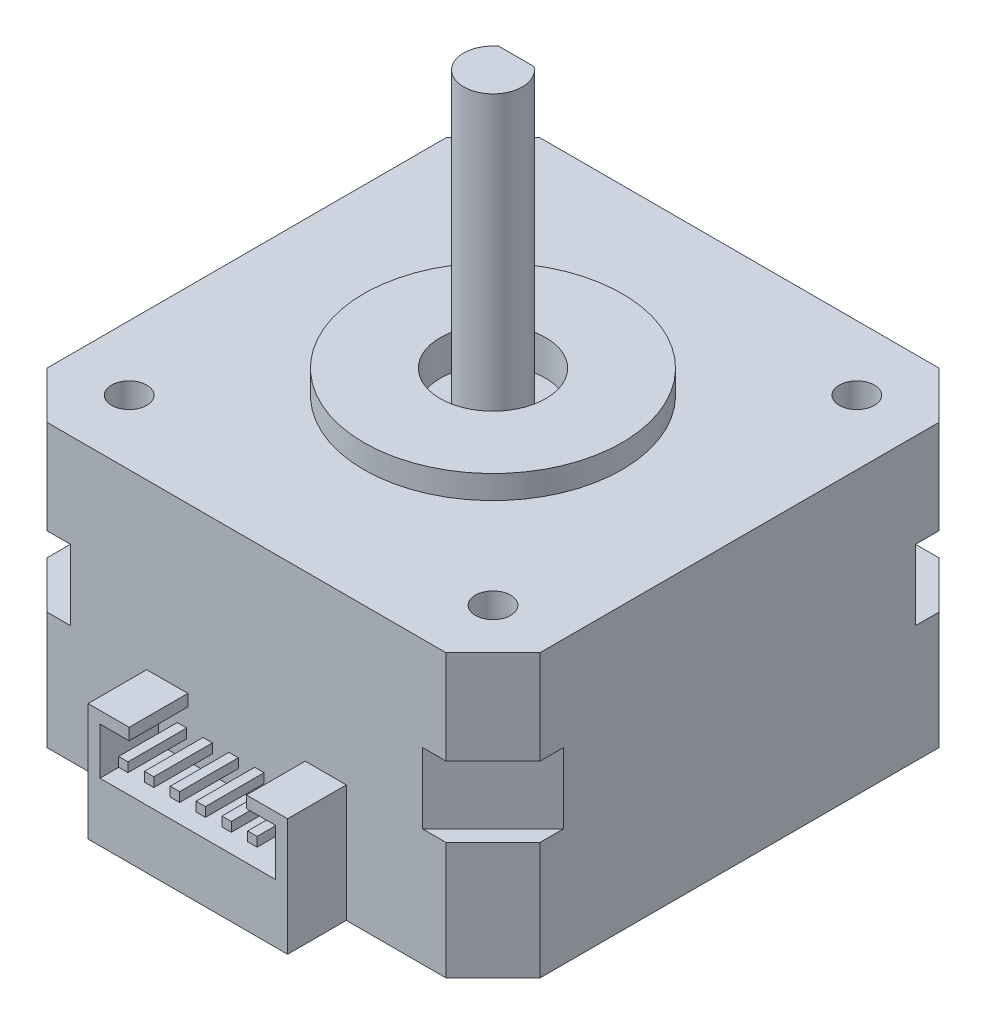
SolidWorks part; units mm, degrees
ref_plane "前视基准面" through (0, 0, 0) normal (0, 0, 1) x (1, 0, 0)
ref_plane "上视基准面" through (0, 0, 0) normal (0, 1, 0) x (1, 0, 0)
ref_plane "右视基准面" through (0, 0, 0) normal (1, 0, 0) x (0, 0, -1)
sketch "草图1" plane through (0, 0, 0) normal (0, 1, 0) x (1, 0, 0)
  line L0 (17, 21) -> (21, 17)
  line L1 (-17, -21) -> (17, -21)
  line L2 (-21, -17) -> (-21, 17)
  line L3 (-17, 21) -> (17, 21)
  line L4 (21, -17) -> (21, 17)
  line L5 (-19, -19) -> (19, 19) construction
  line L6 (-19, 19) -> (19, -19) construction
  line L7 (-21, 17) -> (-17, 21)
  line L8 (-21, -17) -> (-17, -21)
  line L9 (-17, -21) -> (17, -21)
  line L10 (17, -21) -> (21, -17)
  point P0 (0, 0)
extrude "凸台-拉伸1" add sketch "草图1" along normal blind 10 contours L1 L10 L4 L0 L3 L7 L2 L8
sketch "草图3" plane through (0, 10, 0) normal (0, 1, 0) x (1, 0, 0)
  line L0 (15, 21) -> (21, 15)
  line L1 (21, -15) -> (15, -21)
  line L2 (-15, -21) -> (-21, -15)
  line L3 (-21, 15) -> (-15, 21)
  line L8 (-17, -21) -> (17, -21)
  line L9 (17, -21) -> (21, -17)
  line L10 (21, -17) -> (21, 17)
  line L11 (21, 17) -> (17, 21)
  line L12 (17, 21) -> (-17, 21)
  line L13 (-17, 21) -> (-21, 17)
  line L14 (-21, 17) -> (-21, -17)
  line L15 (-21, -17) -> (-17, -21)
  line L16 (-15, -21) -> (15, -21)
  line L18 (21, -15) -> (21, 15)
  line L20 (15, 21) -> (-15, 21)
  line L22 (-21, 15) -> (-21, -15)
  dimension "D2" = 2
  dimension "D3" = 2
  dimension "D1" = 0
  dimension "D4" = 4
extrude "凸台-拉伸2" add sketch "草图3" along normal blind 6
sketch "草图4" plane through (0, 16, 0) normal (0, 1, 0) x (1, 0, 0)
  line L0 (15, 21) -> (17, 21) construction
  line L1 (17, 21) -> (21, 17) construction
  line L2 (21, 15) -> (21, 17) construction
  line L3 (21, -17) -> (21, -15) construction
  line L4 (17, -21) -> (21, -17) construction
  line L5 (15, -21) -> (17, -21) construction
  line L6 (-17, -21) -> (-15, -21) construction
  line L7 (-21, -17) -> (-17, -21) construction
  line L8 (15, 21) -> (-15, 21)
  line L9 (-15, 21) -> (-21, 15)
  line L10 (-21, 15) -> (-21, -15)
  line L11 (-21, -15) -> (-15, -21)
  line L12 (-15, -21) -> (15, -21)
  line L13 (15, -21) -> (21, -15)
  line L14 (21, -15) -> (21, 15)
  line L15 (21, 15) -> (15, 21)
  line L16 (15, 21) -> (-15, 21)
  line L18 (-21, 15) -> (-21, -15)
  line L20 (-15, -21) -> (15, -21)
  line L22 (21, -15) -> (21, 15)
  line L24 (-21, -17) -> (-21, -15) construction
  line L25 (-21, 15) -> (-21, 17) construction
  line L26 (-21, 17) -> (-17, 21) construction
  line L27 (-17, 21) -> (-15, 21) construction
  line L28 (15, 21) -> (17, 21)
  line L29 (17, 21) -> (21, 17)
  line L30 (21, 15) -> (21, 17)
  line L31 (21, -17) -> (21, -15)
  line L32 (17, -21) -> (21, -17)
  line L33 (15, -21) -> (17, -21)
  line L34 (-17, -21) -> (-15, -21)
  line L35 (-21, -17) -> (-17, -21)
  line L36 (-21, -17) -> (-21, -15)
  line L37 (-21, 15) -> (-21, 17)
  line L38 (-21, 17) -> (-17, 21)
  line L39 (-17, 21) -> (-15, 21)
  dimension "D1" = 0
extrude "凸台-拉伸3" add sketch "草图4" along normal blind 8
sketch "草图5" plane through (0, 24, 0) normal (0, 1, 0) x (1, 0, 0)
  circle A0 centre (0, 0) radius 11
  dimension "D1" = 22
extrude "凸台-拉伸4" add sketch "草图5" along normal blind 2
sketch "草图6" plane through (0, 26, 0) normal (0, 1, 0) x (1, 0, 0)
  circle A0 centre (0, 0) radius 4.5
  dimension "D1" = 9
extrude "切除-拉伸1" cut sketch "草图6" against normal blind 3
sketch "草图7" plane through (0, 23, 0) normal (0, 1, 0) x (1, 0, 0)
  circle A0 centre (0, 0) radius 2.5
  dimension "D1" = 5
extrude "凸台-拉伸5" add sketch "草图7" along normal blind 25
sketch "草图8" plane through (0, 48, 0) normal (0, 1, 0) x (1, 0, 0)
  line L0 (-1.5, 2) -> (1.5, 2)
  circle A0 centre (0, 0) radius 2.5 construction
  circle A1 centre (0, 0) radius 2.5 construction
  arc A2 (1.5, 2) -> (-1.5, 2) centre (0, 0) ccw
  dimension "D1" = 2
extrude "切除-拉伸2" cut sketch "草图8" against normal blind 22
sketch "草图9" plane through (0, 24, 0) normal (0, 1, 0) x (1, 0, 0)
  line L0 (-19, 19) -> (-11.9232, 11.9232) construction
  line L1 (-17, 21) -> (-21, 17) construction
  line L2 (19, 19) -> (12.2317, 12.2317) construction
  line L3 (21, 17) -> (17, 21) construction
  circle A0 centre (-15.5, 15.5) radius 1.5
  circle A1 centre (15.5, 15.5) radius 1.5
  circle A2 centre (15.5, -15.5) radius 1.5
  circle A3 centre (-15.5, -15.5) radius 1.5
  dimension "D1" = 3
  dimension "D2" = 31
  dimension "D3" = 31
  dimension "D4" = 31
extrude "切除-拉伸3" cut sketch "草图9" against normal blind 10
sketch "草图10" plane through (0, 0, 21) normal (0, 0, 1) x (1, 0, 0)
  line L0 (-17, 0) -> (17, 0) construction
  line L1 (-8.5, 10) -> (8.5, 10)
  line L2 (-8.5, 10) -> (-8.5, 0)
  line L3 (-8.5, 0) -> (8.5, 0)
  line L4 (8.5, 10) -> (8.5, 0)
  line L5 (-8.5, 10) -> (8.5, 0) construction
  line L6 (-8.5, 0) -> (8.5, 10) construction
  point P0 (0, 5)
  dimension "D1" = 17
  dimension "D2" = 10
extrude "凸台-拉伸6" add sketch "草图10" along normal blind 5
sketch "草图11" plane through (0, 0, 26) normal (0, 0, 1) x (1, 0, 0)
  line L1 (-7.4868, 5) -> (7.4868, 5)
  line L2 (-7.4868, 5) -> (-7.4868, 9)
  line L3 (-7.4868, 9) -> (7.4868, 9)
  line L4 (7.4868, 5) -> (7.4868, 9)
  line L5 (-7.4868, 5) -> (7.4868, 9) construction
  line L6 (-7.4868, 9) -> (7.4868, 5) construction
  point P0 (0, 7)
  dimension "D1" = 4
  dimension "D2" = 7
extrude "切除-拉伸4" cut sketch "草图11" against normal blind 5
sketch "草图12" plane through (0, 0, 26) normal (0, 0, 1) x (1, 0, 0)
  line L0 (7.4868, 9) -> (-7.4868, 9) construction
  line L1 (-5, 10.2246) -> (5, 10.2246)
  line L2 (-5, 10.2246) -> (-5, 9)
  line L3 (-5, 9) -> (5, 9)
  line L4 (5, 10.2246) -> (5, 9)
  line L5 (-5, 10.2246) -> (5, 9) construction
  line L6 (-5, 9) -> (5, 10.2246) construction
  point P0 (0, 9.6123)
  dimension "D1" = 10
extrude "切除-拉伸5" cut sketch "草图12" against normal blind 5
sketch "草图13" plane through (0, 0, 21) normal (0, 0, 1) x (1, 0, 0)
  line L0 (0, 0) -> (0, 10.0959) construction
  line L1 (-8.5, 0) -> (8.5, 0) construction
  line L2 (-7.4868, 9) -> (-7.4868, 5) construction
  line L3 (-5.9, 7.4) -> (-5.1, 7.4)
  line L4 (-5.9, 7.4) -> (-5.9, 6.6)
  line L5 (-5.9, 6.6) -> (-5.1, 6.6)
  line L6 (-5.1, 7.4) -> (-5.1, 6.6)
  line L7 (-5.9, 7.4) -> (-5.1, 6.6) construction
  line L8 (-5.9, 6.6) -> (-5.1, 7.4) construction
  line L9 (-3.7, 7.4) -> (-2.9, 7.4)
  line L10 (-3.7, 7.4) -> (-3.7, 6.6)
  line L11 (-3.7, 6.6) -> (-2.9, 6.6)
  line L12 (-2.9, 7.4) -> (-2.9, 6.6)
  line L13 (-3.7, 7.4) -> (-2.9, 6.6) construction
  line L14 (-3.7, 6.6) -> (-2.9, 7.4) construction
  line L15 (-1.5, 7.4) -> (-0.7, 7.4)
  line L16 (-1.5, 7.4) -> (-1.5, 6.6)
  line L17 (-1.5, 6.6) -> (-0.7, 6.6)
  line L18 (-0.7, 7.4) -> (-0.7, 6.6)
  line L19 (-1.5, 7.4) -> (-0.7, 6.6) construction
  line L20 (-1.5, 6.6) -> (-0.7, 7.4) construction
  line L21 (1.5, 6.6) -> (0.7, 7.4) construction
  line L22 (1.5, 7.4) -> (0.7, 6.6) construction
  line L23 (3.7, 6.6) -> (2.9, 7.4) construction
  line L24 (3.7, 7.4) -> (2.9, 6.6) construction
  line L25 (5.9, 6.6) -> (5.1, 7.4) construction
  line L26 (5.9, 7.4) -> (5.1, 6.6) construction
  line L27 (0.7, 7.4) -> (0.7, 6.6)
  line L28 (1.5, 6.6) -> (0.7, 6.6)
  line L29 (1.5, 7.4) -> (1.5, 6.6)
  line L30 (1.5, 7.4) -> (0.7, 7.4)
  line L31 (2.9, 7.4) -> (2.9, 6.6)
  line L32 (3.7, 6.6) -> (2.9, 6.6)
  line L33 (3.7, 7.4) -> (3.7, 6.6)
  line L34 (3.7, 7.4) -> (2.9, 7.4)
  line L35 (5.1, 7.4) -> (5.1, 6.6)
  line L36 (5.9, 6.6) -> (5.1, 6.6)
  line L37 (5.9, 7.4) -> (5.9, 6.6)
  line L38 (5.9, 7.4) -> (5.1, 7.4)
  point P4 (-5.5, 7)
  point P11 (-7.4868, 7)
  point P13 (-3.3, 7)
  point P18 (-1.1, 7)
  point P34 (1.1, 7)
  point P35 (3.3, 7)
  point P36 (5.5, 7)
  dimension "D1" = 0.8
  dimension "D3" = 1.1
  dimension "D4" = 2.2
  dimension "D2" = 3
extrude "凸台-拉伸7" add sketch "草图13" along normal blind 5
